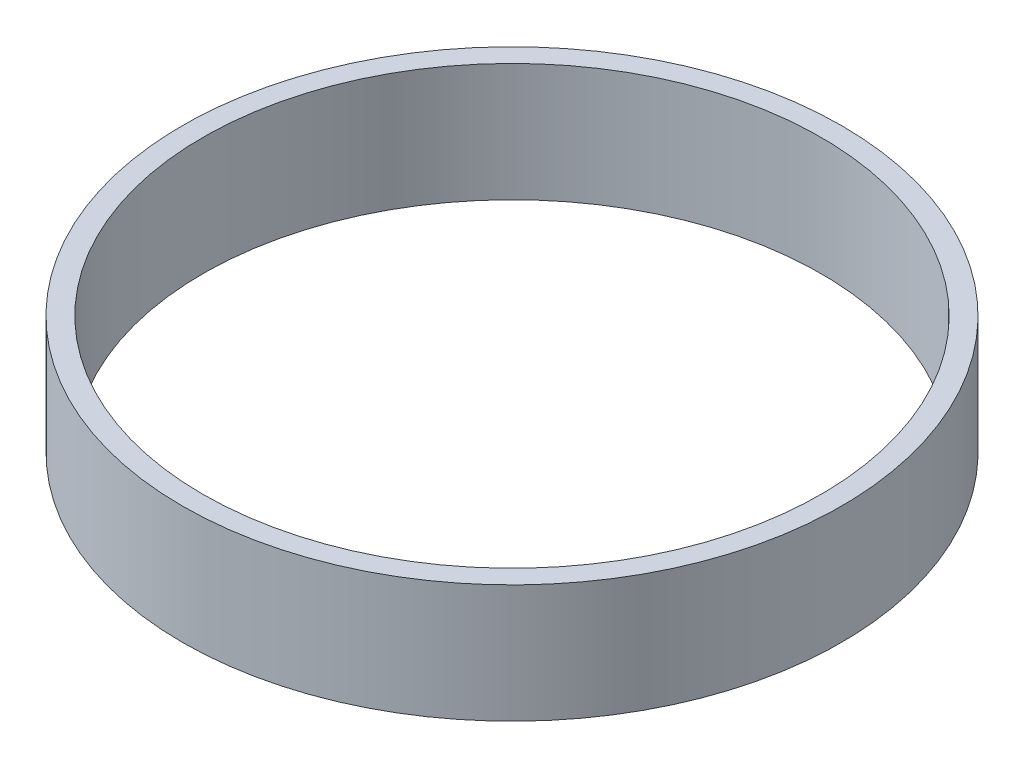
SolidWorks part; units mm, degrees
ref_plane "Front Plane" through (0, 0, 0) normal (0, 0, 1) x (1, 0, 0)
ref_plane "Top Plane" through (0, 0, 0) normal (0, 1, 0) x (1, 0, 0)
ref_plane "Right Plane" through (0, 0, 0) normal (1, 0, 0) x (0, 0, -1)
sketch "Sketch1" plane through (0, 0, 0) normal (0, 1, 0) x (1, 0, 0)
  circle A0 centre (0, 0) radius 38.1
  circle A1 centre (0, 0) radius 35.74
  dimension "D1" = 76.2
  dimension "D2" = 71.48
extrude "Boss-Extrude1" add sketch "Sketch1" along normal blind 13.65
